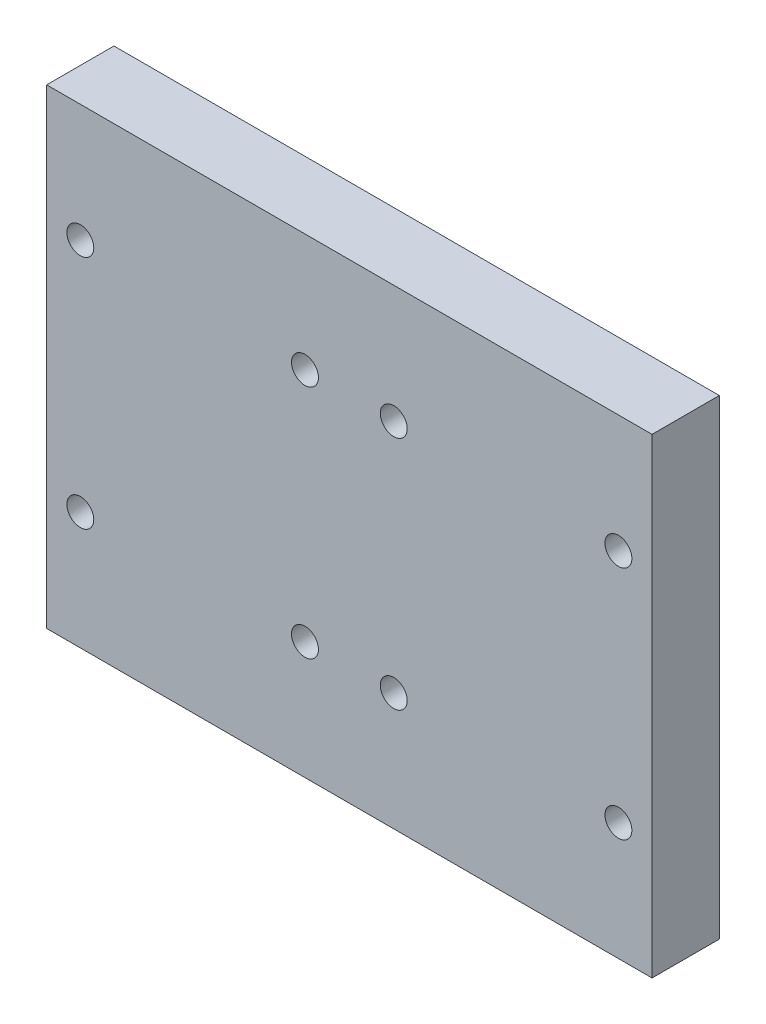
SolidWorks part; units mm, degrees
ref_plane "Plan de face" through (0, 0, 0) normal (0, 0, 1) x (1, 0, 0)
ref_plane "Plan de dessus" through (0, 0, 0) normal (0, 1, 0) x (1, 0, 0)
ref_plane "Plan de droite" through (0, 0, 0) normal (1, 0, 0) x (0, 0, -1)
sketch "Esquisse1" plane through (0, 0, 0) normal (0, 0, 1) x (1, 0, 0)
  line L0 (43, 0) -> (43, -70) construction
  line L1 (0, 0) -> (86, 0)
  line L2 (0, 0) -> (0, -70)
  line L3 (0, -70) -> (86, -70)
  line L4 (86, 0) -> (86, -70)
  circle A0 centre (3, -17.5) radius 2
  circle A1 centre (3, -52.5) radius 2
  circle A2 centre (36.4, -52.5) radius 2
  circle A3 centre (36.4, -17.5) radius 2
  circle A4 centre (49.6, -52.5) radius 2
  circle A5 centre (83, -52.5) radius 2
  circle A6 centre (83, -17.5) radius 2
  circle A7 centre (49.6, -17.5) radius 2
  dimension "D3" = 4
  dimension "D4" = 4
  dimension "D5" = 4
  dimension "D6" = 4
  dimension "D1" = 86
  dimension "D2" = 70
  dimension "D7" = 33.4
  dimension "D8" = 33.4
  dimension "D9" = 35
  dimension "D10" = 35
  dimension "D11" = 17.5
  dimension "D12" = 17.5
  dimension "D13" = 3
  dimension "D14" = 3
extrude "Boss.-Extru.1" add sketch "Esquisse1" along normal blind 10
sketch "Sketch1" plane through (0, 0, 0) normal (0, 0, -1) x (-1, 0, 0)
  line L0 (-86, 0) -> (0, 0) construction
  line L1 (0, 0) -> (2, 0)
  line L2 (0, 0) -> (0, -70) construction
  line L3 (0, 0) -> (0, -70)
  line L4 (2, 0) -> (2, -70)
  line L5 (2, -75) -> (2, 0) construction
  line L6 (2, -70) -> (0, -70)
  line L8 (-86, -70) -> (-86, 0) construction
  line L9 (-88, 0) -> (-86, 0)
  line L10 (-86, -70) -> (-86, 0)
  line L11 (-88, 0) -> (-88, -70)
  line L12 (-88, 0) -> (-88, -75) construction
  line L13 (-88, -70) -> (-86, -70)
extrude "Boss-Extrude2" add sketch "Sketch1" against normal blind 10
